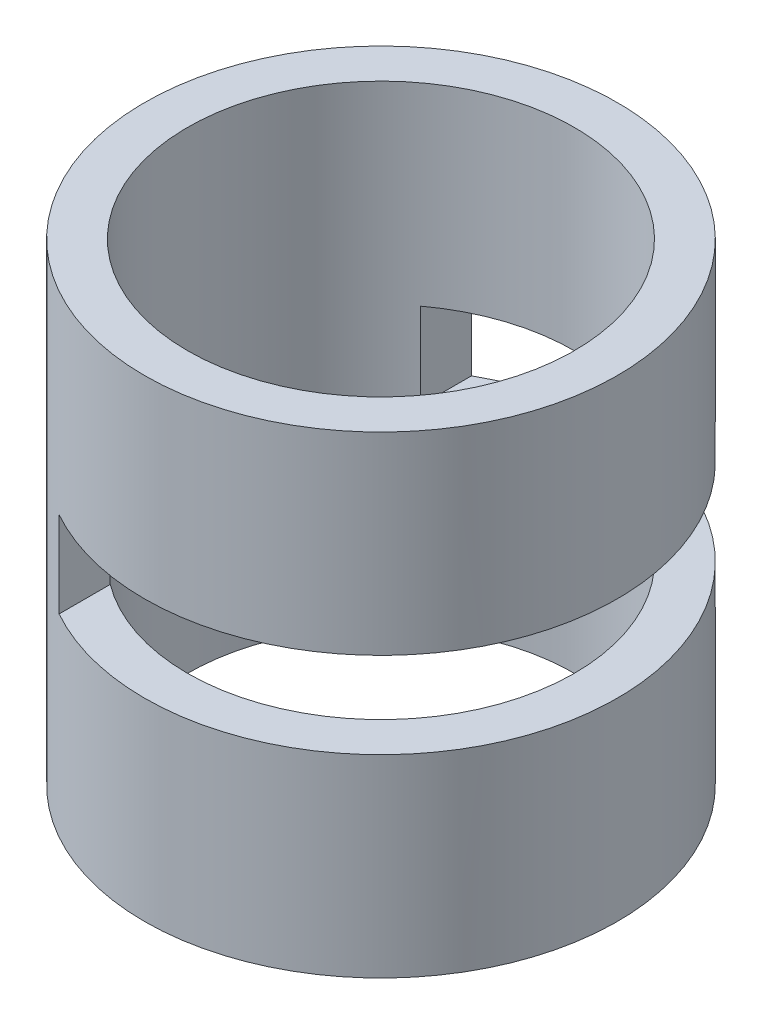
SolidWorks part; units mm, degrees
ref_plane "前视基准面" through (0, 0, 0) normal (0, 0, 1) x (1, 0, 0)
ref_plane "上视基准面" through (0, 0, 0) normal (0, 1, 0) x (1, 0, 0)
ref_plane "右视基准面" through (0, 0, 0) normal (1, 0, 0) x (0, 0, -1)
sketch "草图1" plane through (0, 0, 0) normal (0, 0, 1) x (1, 0, 0)
  line L0 (0, 25.5105) -> (0, -3.6067) construction
  line L1 (9, 22) -> (11, 22)
  line L2 (9, 22) -> (9, 0)
  line L3 (9, 0) -> (11, 0)
  line L4 (11, 22) -> (11, 0)
  dimension "D1" = 9
  dimension "D2" = 11
  dimension "D3" = 22
revolve "旋转1" add sketch "草图1" angle 360 about L0
sketch "草图2" plane through (0, 0, 0) normal (0, 0, 1) x (1, 0, 0)
  line L0 (-11, 0) -> (11, 0) construction
  line L1 (-5.38, 13) -> (11.62, 13)
  line L2 (-5.38, 13) -> (-5.38, 9)
  line L3 (-5.38, 9) -> (11.62, 9)
  line L4 (11.62, 13) -> (11.62, 9)
  line L5 (11, 0) -> (11, 22) construction
  dimension "D1" = 9
  dimension "D2" = 13
  dimension "D3" = 16.38
  dimension "D4" = 17
extrude "切除-拉伸1" cut sketch "草图2" against normal through all and the other way through all
